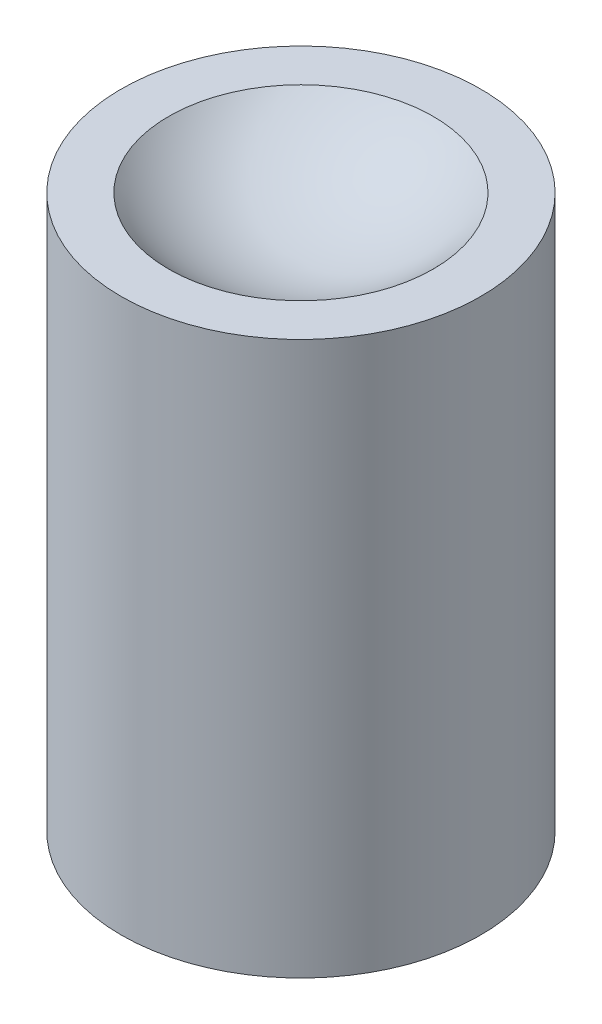
SolidWorks part; units mm, degrees
ref_plane "Front Plane" through (0, 0, 0) normal (0, 0, 1) x (1, 0, 0)
ref_plane "Top Plane" through (0, 0, 0) normal (0, 1, 0) x (1, 0, 0)
ref_plane "Right Plane" through (0, 0, 0) normal (1, 0, 0) x (0, 0, -1)
sketch "Sketch1" plane through (0, 0, 0) normal (0, 1, 0) x (1, 0, 0)
  circle A0 centre (0, 0) radius 6.5
extrude "Boss-Extrude1" add sketch "Sketch1" along normal blind 20
sketch "Sketch2" plane through (0, 0, 0) normal (0, -1, 0) x (1, 0, 0)
  circle A0 centre (0, 0) radius 2
extrude "Cut-Extrude1" cut sketch "Sketch2" against normal blind 7
sketch "Sketch3" plane through (0, 0, 0) normal (0, 0, 1) x (1, 0, 0)
  line L0 (0, 20) -> (0, 17.9) construction
  line L1 (6.5, 20) -> (-6.5, 20) construction
  line L2 (0, 30.9) -> (0, 17.9)
  arc A0 (0, 30.9) -> (0, 17.9) centre (0, 24.4) ccw
  point P8 (0, 24.4)
  dimension "D1" = 2.1
  dimension "D2" = 13
revolve "Cut-Revolve1" cut sketch "Sketch3" angle 360 about L0
